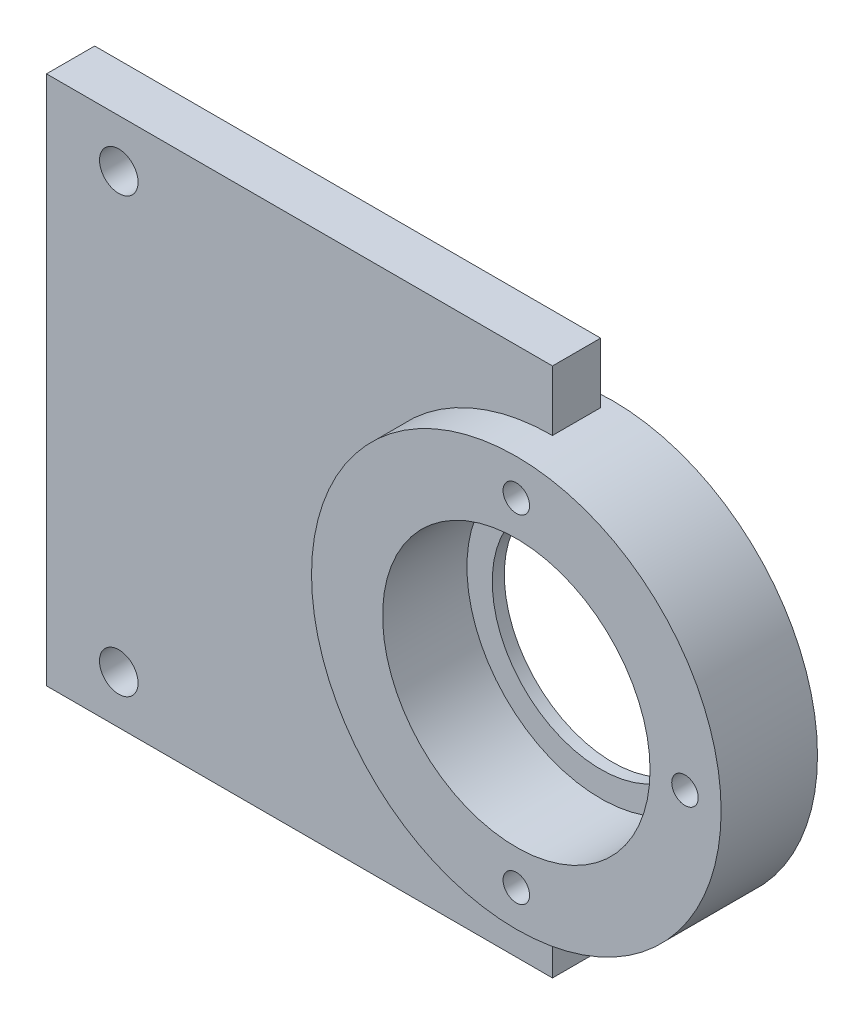
SolidWorks part; units mm, degrees
ref_plane "Front Plane" through (0, 0, 0) normal (0, 0, 1) x (1, 0, 0)
ref_plane "Top Plane" through (0, 0, 0) normal (0, 1, 0) x (1, 0, 0)
ref_plane "Right Plane" through (0, 0, 0) normal (1, 0, 0) x (0, 0, -1)
sketch "Bearing_housing_profile" plane through (0, 0, 0) normal (0, 0, 1) x (1, 0, 0)
  circle A0 centre (0, 0) radius 17
  circle A1 centre (0, 0) radius 11.1
  dimension "D1" = 34
  dimension "D2" = 22.2
extrude "Bearing_housing" add sketch "Bearing_housing_profile" along normal blind 7
sketch "Mounting_web_profile" plane through (0, 0, 0) normal (0, 0, 1) x (1, 0, 0)
  line L1 (-42, -22) -> (0, -22)
  line L2 (-42, -22) -> (-42, 22)
  line L3 (-42, 22) -> (0, 22)
  line L4 (0, -22) -> (0, 22)
  dimension "D1" = 42
  dimension "D2" = 44
extrude "Mounting_web" add sketch "Mounting_web_profile" along normal blind 4
sketch "Bearing_seat_profile" plane through (0, 0, 0) normal (0, 0, 1) x (1, 0, 0)
  circle A0 centre (0, 0) radius 11.1
  dimension "D1" = 22.2
extrude "Bearing_seat" cut sketch "Bearing_seat_profile" along normal through all from offset 50
sketch "Inner_outer_race_retaining_lip_profile" plane through (0, 0, 0) normal (0, 0, 1) x (1, 0, 0)
  circle A0 centre (0, 0) radius 17
  circle A1 centre (0, 0) radius 9
  dimension "D1" = 34
  dimension "D2" = 18
extrude "Inner_outer_race_retaining_lip" add sketch "Inner_outer_race_retaining_lip_profile" along normal blind 1 from offset 1
sketch "Standoff_fasteners_profile" plane through (0, 0, 0) normal (0, 0, 1) x (1, 0, 0)
  circle A0 centre (-36, -18) radius 1.6
  circle A1 centre (-36, 18) radius 1.6
  dimension "D1" = 3.2
  dimension "D2" = 3.2
extrude "Standoff_fasteners" cut sketch "Standoff_fasteners_profile" along normal through all from offset 50
sketch "Bearing_keeper_fasteners_profile" plane through (0, 0, 0) normal (0, 0, 1) x (1, 0, 0)
  circle A0 centre (14, 0) radius 1.1
  circle A1 centre (0, -14) radius 1.1
  circle A2 centre (0, 14) radius 1.1
  dimension "D1" = 2.2
  dimension "D2" = 2.2
  dimension "D3" = 2.2
extrude "Bearing_keeper_fasteners" cut sketch "Bearing_keeper_fasteners_profile" along normal through all from offset 50
